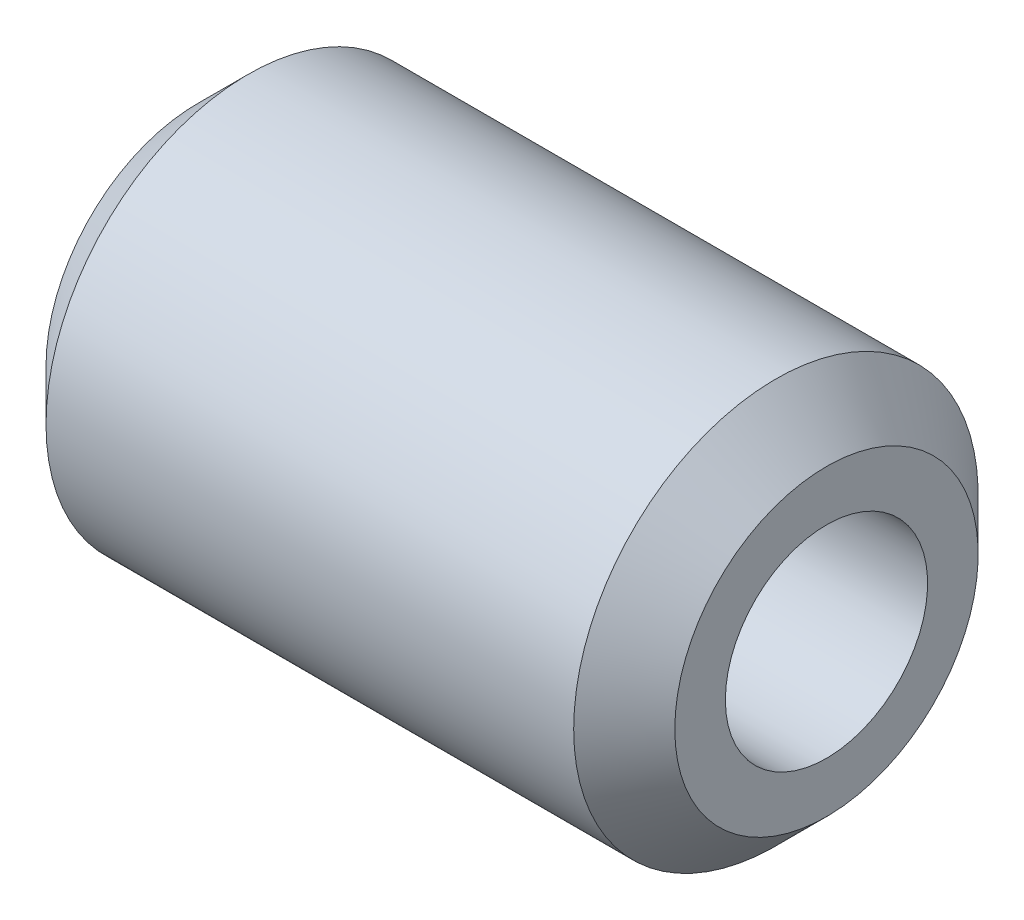
SolidWorks part; units mm, degrees
ref_plane "Front Plane" through (0, 0, 0) normal (0, 0, 1) x (1, 0, 0)
ref_plane "Top Plane" through (0, 0, 0) normal (0, 1, 0) x (1, 0, 0)
ref_plane "Right Plane" through (0, 0, 0) normal (1, 0, 0) x (0, 0, -1)
sketch "Sketch1" plane through (0, 0, 0) normal (0, 0, 1) x (1, 0, 0)
  line L0 (-73.004, 0) -> (55.1955, 0) construction
  line L1 (-17.1, 5.5) -> (-17.1, 8.25)
  line L2 (-17.1, 8.25) -> (-14.35, 11)
  line L3 (-14.35, 11) -> (14.35, 11)
  line L4 (14.35, 11) -> (17.1, 8.25)
  line L5 (17.1, 8.25) -> (17.1, 5.5)
  line L6 (17.1, 5.5) -> (-17.1, 5.5)
  line L7 (0, 5.5) -> (0, 0) construction
  line L8 (0, 5.5) -> (0, 11) construction
  line L9 (-17.1, 8.25) -> (17.1, 8.25) construction
  dimension "D1" = 5.5
  dimension "D2" = 34.2
  dimension "D3" = 8.25
  dimension "D4" = 2.75
  dimension "D5" = 45
revolve "Revolve1" add sketch "Sketch1" angle 360 about L0
